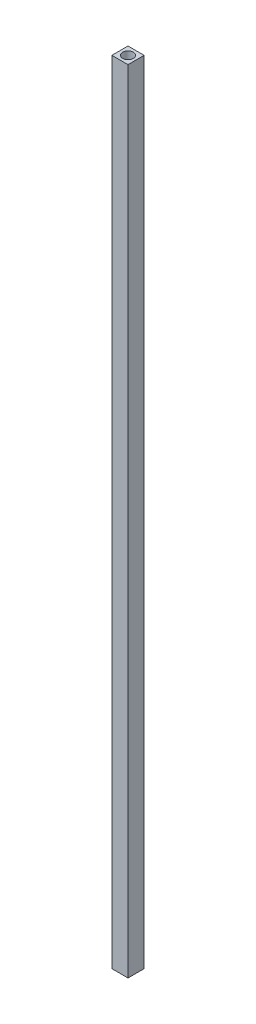
SolidWorks part; units mm, degrees
material "Thornel Mat VMA"
ref_plane "前视基准面" through (0, 0, 0) normal (0, 0, 1) x (1, 0, 0)
ref_plane "上视基准面" through (0, 0, 0) normal (0, 1, 0) x (1, 0, 0)
ref_plane "右视基准面" through (0, 0, 0) normal (1, 0, 0) x (0, 0, -1)
other "Configuration Table"
sketch "草图1" plane through (0, 0, 0) normal (0, 1, 0) x (1, 0, 0)
  line L0 (0, 0) -> (3, -3) construction
  line L1 (0, 0) -> (3, 0)
  line L2 (0, 0) -> (0, -3)
  line L3 (0, -3) -> (3, -3)
  line L4 (3, 0) -> (3, -3)
  line L5 (3, 0) -> (0, -3) construction
  circle A0 centre (1.5, -1.5) radius 1
  dimension "D3" = 2
  dimension "D1" = 3
  dimension "D2" = 3
extrude "凸台-拉伸1" add sketch "草图1" along normal blind 147
